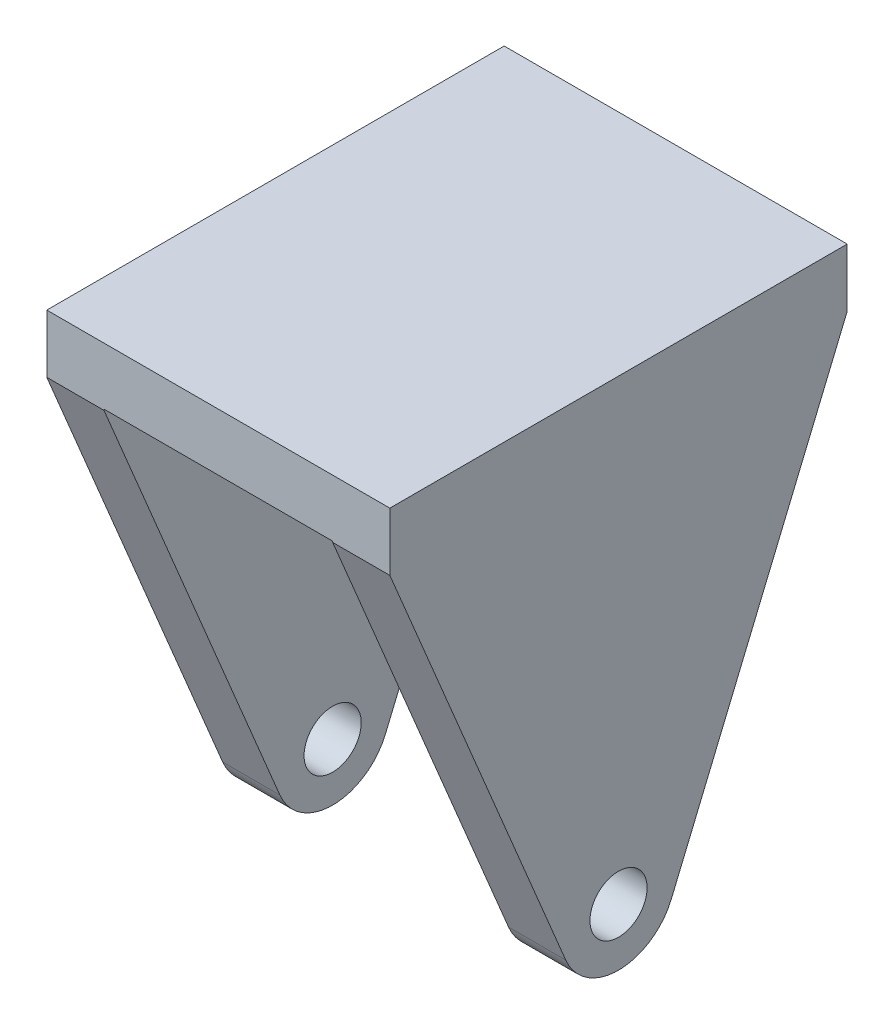
SolidWorks part; units mm, degrees
ref_plane "Front" through (0, 0, 0) normal (0, 0, 1) x (1, 0, 0)
ref_plane "Top" through (0, 0, 0) normal (0, 1, 0) x (1, 0, 0)
ref_plane "Right" through (0, 0, 0) normal (1, 0, 0) x (0, 0, -1)
sketch "Sketch1" plane through (0, 0, 0) normal (0, 0, 1) x (1, 0, 0)
  line L0 (52.4581, -3.175) -> (52.4581, -60.325)
  line L1 (98.65, -3.175) -> (-98.65, -3.175) construction
  line L2 (52.4581, -60.325) -> (46.1081, -60.325)
  line L3 (46.1081, -60.325) -> (46.1081, -9.525)
  line L4 (46.1081, -9.525) -> (20.7081, -9.525)
  line L5 (20.7081, -9.525) -> (20.7081, -60.325)
  line L6 (20.7081, -60.325) -> (14.3581, -60.325)
  line L7 (14.3581, -60.325) -> (14.3581, -3.175)
  line L8 (14.3581, -3.175) -> (52.4581, -3.175)
  point P10 (18.8584, -60.325)
  dimension "D1" = 6.35
  dimension "D2" = 57.15
  dimension "D3" = 6.35
  dimension "D4" = 25.4
extrude "Boss-Extrude1" add sketch "Sketch1" against normal blind 50.8
sketch "Sketch2" plane through (14.3581, 0, 0) normal (-1, 0, 0) x (0, 0, 1)
  line L0 (-25.4, -3.175) -> (-25.4, -60.325)
  line L1 (-50.8, -3.175) -> (0, -3.175) construction
  line L2 (-50.8, -60.325) -> (0, -60.325) construction
  line L3 (-50.8, -9.525) -> (0, -9.525) construction
  line L4 (-19.5407, -56.4226) -> (0, -9.6438)
  line L5 (0, -3.175) -> (0, -60.325) construction
  line L6 (-31.2593, -56.4226) -> (-50.8, -9.6438)
  line L7 (-50.8, -3.175) -> (-50.8, -60.325) construction
  circle A0 centre (-25.4, -53.975) radius 6.35
  circle A1 centre (-25.4, -53.975) radius 3.175
  line M1 (0, -60.325) -> (0, -3.175)
  line M3 (-50.8, -3.175) -> (-50.8, -60.325)
  line M4 (-50.8, -60.325) -> (0, -60.325)
  dimension "D2" = 6.35
  dimension "D1" = 44.45
extrude "Cut-Extrude1" cut sketch "Sketch2" against normal up to surface (38.1 mm away) contours L0 A1 | L0 A1 | A0 L4 M4 M1 | A0 L6 M3 M4 up to face at (52.4581, -31.75, -25.4)
